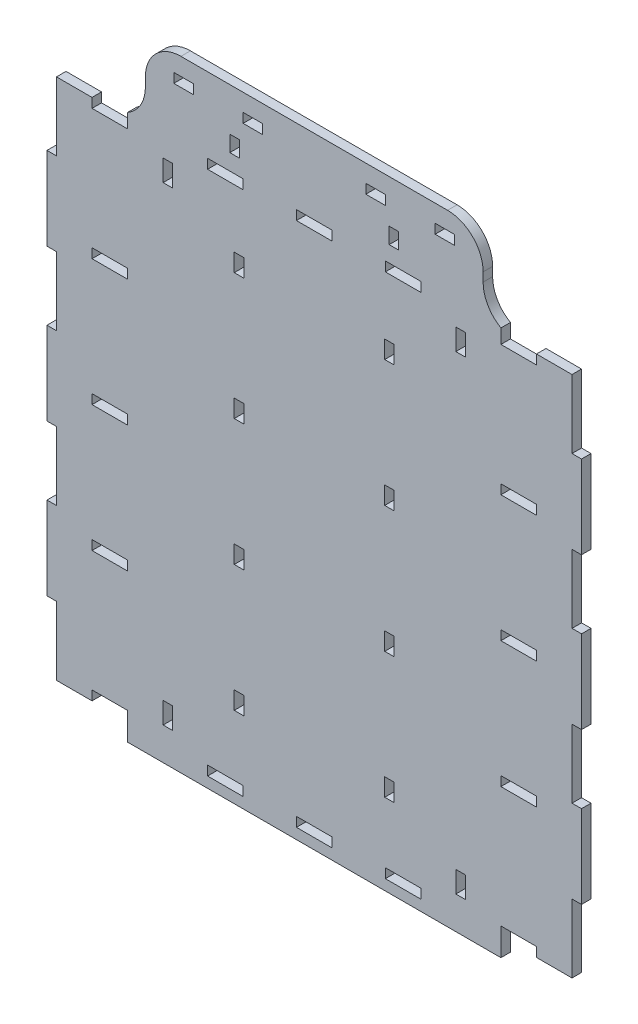
SolidWorks part; units mm, degrees
ref_plane "Front Plane" through (0, 0, 0) normal (0, 0, 1) x (1, 0, 0)
ref_plane "Top Plane" through (0, 0, 0) normal (0, 1, 0) x (1, 0, 0)
ref_plane "Right Plane" through (0, 0, 0) normal (1, 0, 0) x (0, 0, -1)
sketch "Model" plane through (0, 0, 0) normal (0, 0, 1) x (1, 0, 0)
  line L167 (125, 304.11) -> (145, 304.11)
  line L168 (105, 0) -> (105, 15.46)
  line L169 (-145, 10.11) -> (-145, 48.61)
  line L170 (-145, 304.11) -> (-125, 304.11)
  line L171 (145, 10.11) -> (145, 48.61)
  line L172 (0, 0) -> (0, 349.11) construction
  line L173 (-95, 324.11) -> (-95, 329.11)
  line L174 (-75, 349.11) -> (75, 349.11)
  line L175 (95, 324.11) -> (95, 329.11)
  line L176 (125, 304.11) -> (125, 298.76)
  line L177 (105, 298.76) -> (125, 298.76)
  line L178 (-105, 306.7895) -> (-105, 298.76)
  line L179 (-105, 298.76) -> (-125, 298.76)
  line L180 (-125, 304.11) -> (-125, 298.76)
  line L181 (105, 306.7895) -> (105, 298.76)
  line L182 (-105, 0) -> (105, 0)
  line L183 (105, 15.46) -> (125, 15.46)
  line L184 (-105, 0) -> (-105, 15.46)
  line L185 (-105, 15.46) -> (-125, 15.46)
  line L186 (-125, 10.11) -> (-125, 15.46)
  line L187 (125, 10.11) -> (125, 15.46)
  line L188 (-125, 15.46) -> (-125, 10.11)
  line L189 (-125, 10.11) -> (-145, 10.11)
  line L190 (150.35, 157.11) -> (-150.35, 157.11) construction
  line L191 (125, 10.11) -> (145, 10.11)
  line L192 (-125, 159.785) -> (-105, 159.785)
  line L193 (-125, 159.785) -> (-125, 154.435)
  line L194 (-125, 154.435) -> (-105, 154.435)
  line L195 (-105, 159.785) -> (-105, 154.435)
  line L196 (-145, 180.4433) -> (-150.35, 180.4433)
  line L197 (-145, 265.61) -> (-150.35, 265.61)
  line L198 (-145, 133.7767) -> (-150.35, 133.7767)
  line L199 (-150.35, 180.4433) -> (-150.35, 133.7767)
  line L200 (-145, 180.4433) -> (-145, 218.9433)
  line L201 (-150.35, 265.61) -> (-150.35, 218.9433)
  line L202 (-145, 218.9433) -> (-150.35, 218.9433)
  line L203 (-145, 95.2767) -> (-150.35, 95.2767)
  line L204 (-150.35, 95.2767) -> (-150.35, 48.61)
  line L205 (-145, 48.61) -> (-150.35, 48.61)
  line L206 (-145, 265.61) -> (-145, 304.11)
  line L207 (-145, 95.2767) -> (-145, 133.7767)
  line L208 (-125, 230.865) -> (-125, 225.515)
  line L209 (-125, 225.515) -> (-105, 225.515)
  line L210 (-105, 230.865) -> (-105, 225.515)
  line L211 (-125, 230.865) -> (-105, 230.865)
  line L212 (-125, 88.705) -> (-125, 83.355)
  line L213 (-125, 83.355) -> (-105, 83.355)
  line L214 (-105, 88.705) -> (-105, 83.355)
  line L215 (-125, 88.705) -> (-105, 88.705)
  line L216 (-39.65, 197.65) -> (-39.65, 187.65)
  line L217 (-45, 268.73) -> (-39.65, 268.73)
  line L218 (-45, 268.73) -> (-45, 258.73)
  line L219 (-45, 258.73) -> (-39.65, 258.73)
  line L220 (-39.65, 268.73) -> (-39.65, 258.73)
  line L221 (-45, 187.65) -> (-39.65, 187.65)
  line L222 (-45, 197.65) -> (-45, 187.65)
  line L223 (-45, 197.65) -> (-39.65, 197.65)
  line L224 (-39.65, 126.57) -> (-39.65, 116.57)
  line L225 (-45, 116.57) -> (-39.65, 116.57)
  line L226 (-45, 126.57) -> (-45, 116.57)
  line L227 (-45, 126.57) -> (-39.65, 126.57)
  line L228 (-39.65, 55.49) -> (-39.65, 45.49)
  line L229 (-45, 45.49) -> (-39.65, 45.49)
  line L230 (-45, 55.49) -> (-45, 45.49)
  line L231 (-45, 55.49) -> (-39.65, 55.49)
  line L232 (-60, 301.6) -> (-40, 301.6)
  line L233 (-10, 11.35) -> (10, 11.35)
  line L234 (-10, 11.35) -> (-10, 6)
  line L235 (-10, 6) -> (10, 6)
  line L236 (10, 11.35) -> (10, 6)
  line L237 (-85, 294.6) -> (-79.65, 294.6)
  line L238 (-85, 294.6) -> (-85, 282.6)
  line L239 (-85, 282.6) -> (-79.65, 282.6)
  line L240 (-60, 11.35) -> (-40, 11.35)
  line L241 (-40, 11.35) -> (-40, 6)
  line L242 (-60, 6) -> (-40, 6)
  line L243 (-60, 11.35) -> (-60, 6)
  line L244 (-79.65, 294.6) -> (-79.65, 282.6)
  line L245 (-85, 30.35) -> (-79.65, 30.35)
  line L246 (-85, 30.35) -> (-85, 18.35)
  line L247 (-85, 18.35) -> (-79.65, 18.35)
  line L248 (-79.65, 30.35) -> (-79.65, 18.35)
  line L249 (-10, 306.95) -> (10, 306.95)
  line L250 (-10, 306.95) -> (-10, 301.6)
  line L251 (-10, 301.6) -> (10, 301.6)
  line L252 (10, 306.95) -> (10, 301.6)
  line L253 (-40, 306.95) -> (-40, 301.6)
  line L254 (-60, 306.95) -> (-40, 306.95)
  line L255 (-60, 306.95) -> (-60, 301.6)
  line L256 (-79, 339.3) -> (-68, 339.3)
  line L257 (-47.5, 324.95) -> (-42.15, 324.95)
  line L258 (-47.5, 324.95) -> (-47.5, 315.95)
  line L259 (-47.5, 315.95) -> (-42.15, 315.95)
  line L260 (-42.15, 324.95) -> (-42.15, 315.95)
  line L261 (-40, 339.3) -> (-29, 339.3)
  line L262 (-40, 339.3) -> (-40, 333.95)
  line L263 (-40, 333.95) -> (-29, 333.95)
  line L264 (-29, 339.3) -> (-29, 333.95)
  line L265 (-79, 333.95) -> (-68, 333.95)
  line L266 (-68, 339.3) -> (-68, 333.95)
  line L267 (-79, 339.3) -> (-79, 333.95)
  line L268 (60, 306.95) -> (60, 301.6)
  line L269 (60, 306.95) -> (40, 306.95)
  line L270 (40, 306.95) -> (40, 301.6)
  line L271 (60, 301.6) -> (40, 301.6)
  line L272 (47.5, 315.95) -> (42.15, 315.95)
  line L273 (47.5, 324.95) -> (47.5, 315.95)
  line L274 (47.5, 324.95) -> (42.15, 324.95)
  line L275 (42.15, 324.95) -> (42.15, 315.95)
  line L276 (40, 339.3) -> (40, 333.95)
  line L277 (40, 333.95) -> (29, 333.95)
  line L278 (29, 339.3) -> (29, 333.95)
  line L279 (40, 339.3) -> (29, 339.3)
  line L280 (68, 339.3) -> (68, 333.95)
  line L281 (79, 339.3) -> (79, 333.95)
  line L282 (79, 339.3) -> (68, 339.3)
  line L283 (79, 333.95) -> (68, 333.95)
  line L284 (145, 48.61) -> (150.35, 48.61)
  line L285 (150.35, 95.2767) -> (150.35, 48.61)
  line L286 (145, 95.2767) -> (150.35, 95.2767)
  line L287 (145, 133.7767) -> (150.35, 133.7767)
  line L288 (150.35, 180.4433) -> (150.35, 133.7767)
  line L289 (145, 180.4433) -> (150.35, 180.4433)
  line L290 (145, 218.9433) -> (150.35, 218.9433)
  line L291 (145, 265.61) -> (150.35, 265.61)
  line L292 (150.35, 265.61) -> (150.35, 218.9433)
  line L293 (145, 265.61) -> (145, 304.11)
  line L294 (145, 95.2767) -> (145, 133.7767)
  line L295 (145, 180.4433) -> (145, 218.9433)
  line L296 (125, 88.705) -> (125, 83.355)
  line L297 (105, 88.705) -> (105, 83.355)
  line L298 (125, 88.705) -> (105, 88.705)
  line L299 (125, 83.355) -> (105, 83.355)
  line L300 (125, 159.785) -> (125, 154.435)
  line L301 (105, 159.785) -> (105, 154.435)
  line L302 (125, 154.435) -> (105, 154.435)
  line L303 (125, 159.785) -> (105, 159.785)
  line L304 (125, 230.865) -> (125, 225.515)
  line L305 (105, 230.865) -> (105, 225.515)
  line L306 (125, 230.865) -> (105, 230.865)
  line L307 (125, 225.515) -> (105, 225.515)
  line L308 (85, 294.6) -> (79.65, 294.6)
  line L309 (79.65, 294.6) -> (79.65, 282.6)
  line L310 (85, 294.6) -> (85, 282.6)
  line L311 (85, 282.6) -> (79.65, 282.6)
  line L312 (39.65, 268.73) -> (39.65, 258.73)
  line L313 (45, 268.73) -> (39.65, 268.73)
  line L314 (45, 268.73) -> (45, 258.73)
  line L315 (45, 258.73) -> (39.65, 258.73)
  line L316 (45, 197.65) -> (39.65, 197.65)
  line L317 (45, 197.65) -> (45, 187.65)
  line L318 (39.65, 197.65) -> (39.65, 187.65)
  line L319 (45, 187.65) -> (39.65, 187.65)
  line L320 (45, 126.57) -> (39.65, 126.57)
  line L321 (45, 126.57) -> (45, 116.57)
  line L322 (39.65, 126.57) -> (39.65, 116.57)
  line L323 (45, 116.57) -> (39.65, 116.57)
  line L324 (45, 55.49) -> (45, 45.49)
  line L325 (45, 55.49) -> (39.65, 55.49)
  line L326 (39.65, 55.49) -> (39.65, 45.49)
  line L327 (45, 45.49) -> (39.65, 45.49)
  line L328 (85, 30.35) -> (79.65, 30.35)
  line L329 (85, 30.35) -> (85, 18.35)
  line L330 (79.65, 30.35) -> (79.65, 18.35)
  line L331 (85, 18.35) -> (79.65, 18.35)
  line L332 (60, 11.35) -> (60, 6)
  line L333 (60, 6) -> (40, 6)
  line L334 (60, 11.35) -> (40, 11.35)
  line L335 (40, 11.35) -> (40, 6)
  arc A4 (-105, 306.7895) -> (-95, 324.11) centre (-115, 324.11) ccw
  arc A5 (-75, 349.11) -> (-95, 329.11) centre (-75, 329.11) ccw
  arc A6 (95, 329.11) -> (75, 349.11) centre (75, 329.11) ccw
  arc A7 (95, 324.11) -> (105, 306.7895) centre (115, 324.11) ccw
  point P201 (0, 349.11)
  point P225 (-125, 157.11)
  point P226 (-150.35, 157.11)
  point P263 (0, 11.35)
  point P280 (0, 306.95)
  dimension "D3" = 20
  dimension "D4" = 20
  dimension "D9" = 190
  dimension "D11" = 45
  dimension "D17" = 5.35
  dimension "D18" = 5.35
  dimension "D19" = 290
  dimension "D20" = 10
  dimension "D21" = 304.11
  dimension "D25" = 15.46
  dimension "D26" = 5.35
  dimension "D32" = 5.35
  dimension "D33" = 38.5
  dimension "D35" = 65.73
  dimension "D38" = 65.73
  dimension "D39" = 5.35
  dimension "D41" = 10
  dimension "D44" = 30.03
  dimension "D46" = 100
  dimension "D49" = 61.08
  dimension "D50" = 20
  dimension "D51" = 5.35
  dimension "D53" = 6
  dimension "D58" = 30
  dimension "D54" = 5.35
  dimension "D56" = 12
  dimension "D14" = 60
  dimension "D22" = 9.51
  dimension "D24" = 18.35
  dimension "D29" = 2.84
  dimension "D36" = 30
  dimension "D13" = 5.35
  dimension "D15" = 9
  dimension "D23" = 24.16
  dimension "D40" = 47.5
  dimension "D45" = 11
  dimension "D48" = 5.35
  dimension "D55" = 9.81
  dimension "D60" = 55
  dimension "D63" = 28
  dimension "D30" = 2
  dimension "D31" = 2
  dimension "D28" = 2
  dimension "D37" = 2
  dimension "D47" = 4
  dimension "D57" = 2
  dimension "D34" = 2
  dimension "D61" = 2
extrude "Boss-Extrude1" add sketch "Model" along normal blind 5.35 contours A7 L175 A6 L174 A5 L173 A4 L178 L179 L180 L170 L206 L197 L201 L202 L200 L196 L199 L198 L207 L203 L204 L205 L169 L189 L186 L185 L184 L182 L168 L183 L187 L191 L171 L284 L285 L286 L294 L287 L288 L289 L295 L290 L292 L291 L293 L167 L176 L177 L181
equation "\"mdfthick\"=5.35"
equation "\"D17@Model\"=\"mdfthick\""
equation "\"D18@Model\"=\"mdfthick\""
equation "\"D26@Model\"=\"mdfthick\""
equation "\"D32@Model\"=\"mdfthick\""
equation "\"D39@Model\"=\"mdfthick\""
equation "\"D51@Model\"=\"mdfthick\""
equation "\"D54@Model\"=\"mdfthick\""
equation "\"D13@Model\"=\"mdfthick\""
equation "\"D48@Model\"=\"mdfthick\""
equation "\"D1@Boss-Extrude1\"=\"mdfthick\""
